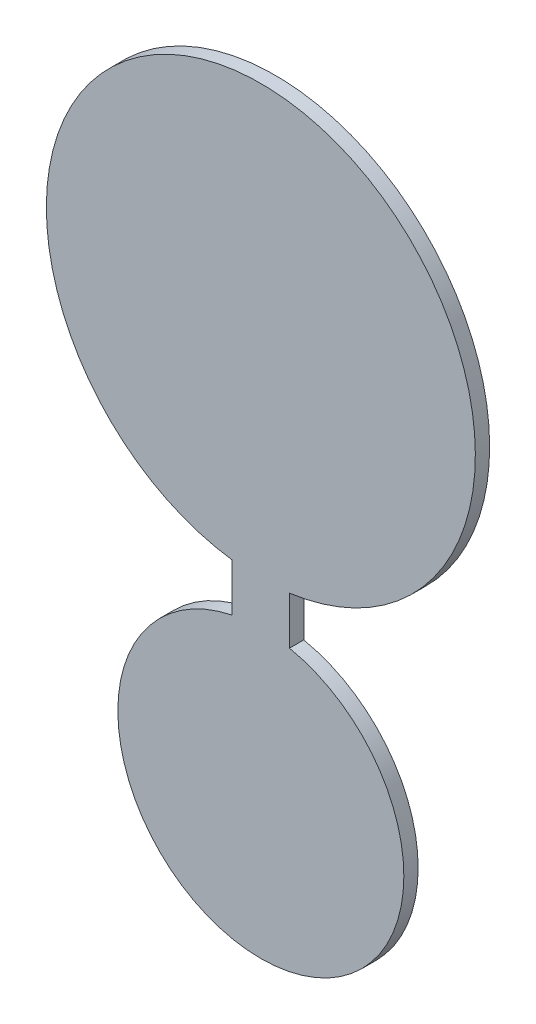
SolidWorks part; units mm, degrees
ref_plane "Front Plane" through (0, 0, 0) normal (0, 0, 1) x (1, 0, 0)
ref_plane "Top Plane" through (0, 0, 0) normal (0, 1, 0) x (1, 0, 0)
ref_plane "Right Plane" through (0, 0, 0) normal (1, 0, 0) x (0, 0, -1)
sketch "Sketch1" plane through (0, 0, 0) normal (0, 0, 1) x (1, 0, 0)
  line L0 (0, 0) -> (0, 280) construction
  line L1 (-20, 0) -> (-20, 280)
  line L2 (20, 0) -> (20, 280)
  circle A0 centre (0, 280) radius 150
  circle A1 centre (0, 0) radius 100
  arc A2 (-20, 0) -> (20, 0) centre (0, 0) ccw
  arc A3 (20, 280) -> (-20, 280) centre (0, 280) ccw
  point P4 (0, 140)
  dimension "D1" = 300
  dimension "D2" = 200
  dimension "D4" = 20
  dimension "D3" = 280
extrude "Boss-Extrude1" add sketch "Sketch1" along normal mid plane 10
